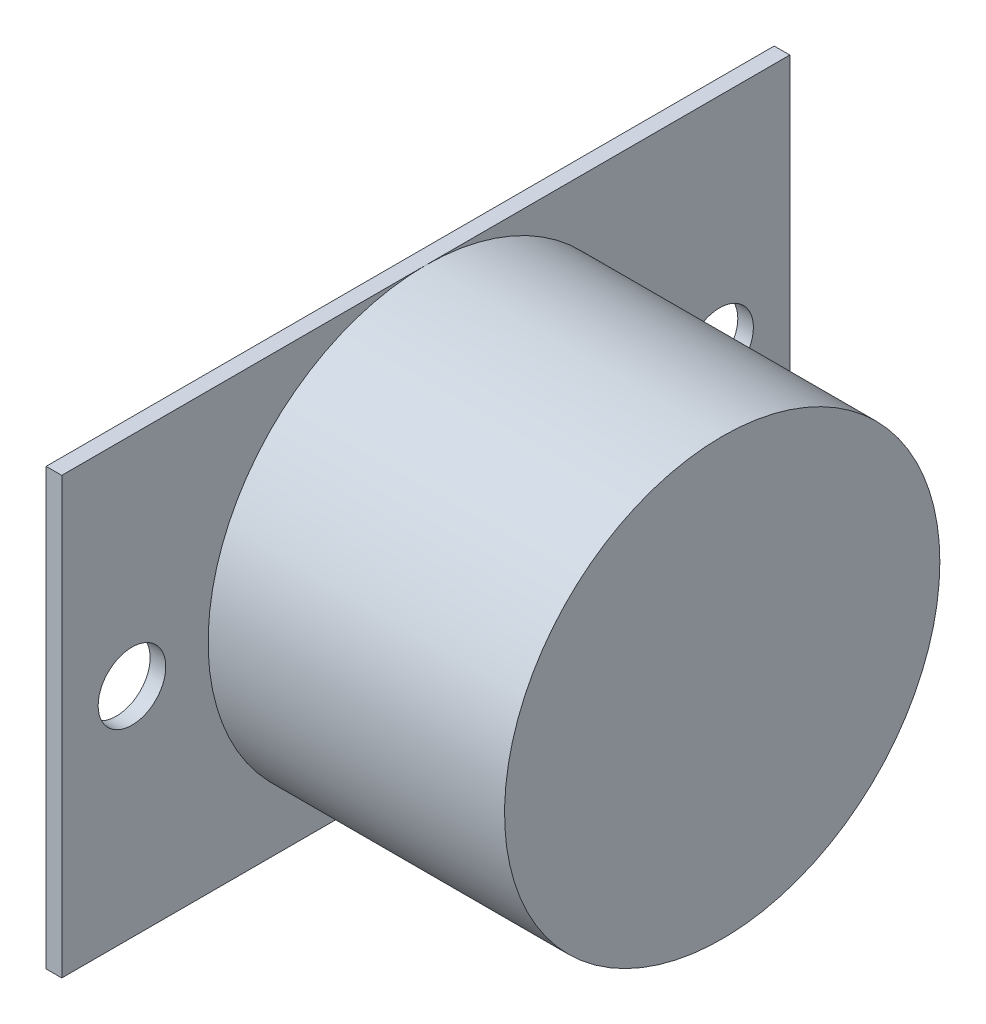
SolidWorks part; units mm, degrees
ref_plane "Front Plane" through (0, 0, 0) normal (0, 0, 1) x (1, 0, 0)
ref_plane "Top Plane" through (0, 0, 0) normal (0, 1, 0) x (1, 0, 0)
ref_plane "Right Plane" through (0, 0, 0) normal (1, 0, 0) x (0, 0, -1)
sketch "Sketch1" plane through (0, 0, 0) normal (1, 0, 0) x (0, 0, -1)
  line L0 (0, 0) -> (35, 0) construction
  circle A0 centre (0, 0) radius 20.9269
extrude "Boss-Extrude2" add sketch "Sketch1" along normal blind 30
sketch "Sketch3" plane through (0, 0, 0) normal (-1, 0, 0) x (0, 0, 1)
  line L0 (25, 0) -> (0, 0) construction
  line L1 (0, 0) -> (32, 0) construction
  line L2 (25, 0) -> (32, 0) construction
  line L3 (0, 20.9269) -> (0, -20.9269) construction
  line L4 (0, 0) -> (35, 0) construction
  line L5 (-35, -20.9269) -> (-35, 20.9269)
  line L6 (-35, -20.9269) -> (35, -20.9269)
  line L7 (0, -20.9269) -> (0, 20.9269)
  line L8 (-35, 20.9269) -> (35, 20.9269)
  line L9 (35, -20.9269) -> (35, 20.9269)
  circle A0 centre (28.5, 0) radius 3.5
  circle A1 centre (0, 0) radius 20.9269 construction
  circle A2 centre (-28.5, 0) radius 3.5
  circle A3 centre (-28.5, 0) radius 3.5
  circle A4 centre (-28.5, 0) radius 3.5
extrude "Boss-Extrude3" add sketch "Sketch3" against normal blind 1.5 contours L8 L9 L6 L5
sketch "Sketch4" plane through (0, 0, 0) normal (-1, 0, 0) x (0, 0, 1)
  line L0 (0, 0) -> (31.5, 0) construction
  line L1 (0, 0) -> (25, 0) construction
  line L2 (0, 20.9269) -> (0, -20.9269) construction
  line L3 (-35, 20.9269) -> (35, 20.9269) construction
  line L4 (-35, -20.9269) -> (35, -20.9269) construction
  line L5 (25, 0) -> (31.5, 0) construction
  line L6 (18.5, 0) -> (31.5, 0) construction
  line L7 (25, 0) -> (31.5, 0) construction
  circle A0 centre (28.25, 0) radius 3.25
  circle A1 centre (-28.25, 0) radius 3.25
  point P13 (25, 0)
extrude "Cut-Extrude1" cut sketch "Sketch4" against normal blind 1.5
